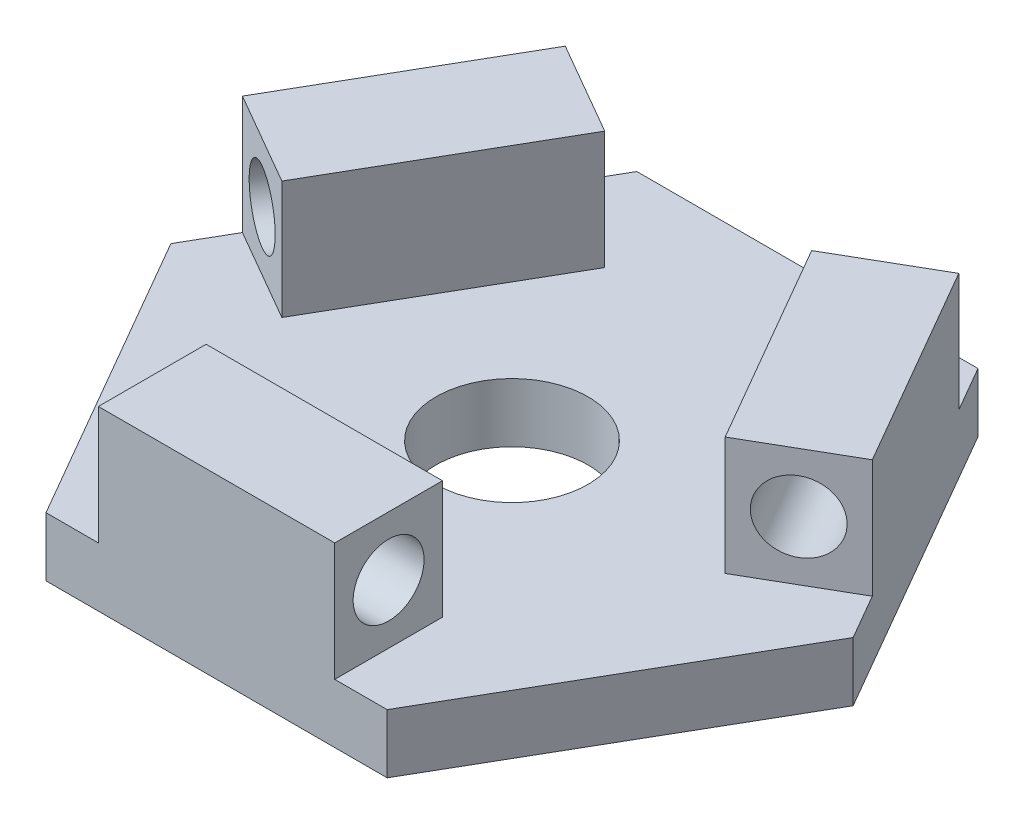
SolidWorks part; units mm, degrees
ref_plane "Front Plane" through (0, 0, 0) normal (0, 0, 1) x (1, 0, 0)
ref_plane "Top Plane" through (0, 0, 0) normal (0, 1, 0) x (1, 0, 0)
ref_plane "Right Plane" through (0, 0, 0) normal (1, 0, 0) x (0, 0, -1)
sketch "Sketch1" plane through (0, 0, 0) normal (0, 1, 0) x (1, 0, 0)
  line L1 (14.4338, 25) -> (-14.4338, 25)
  line L2 (-14.4338, 25) -> (-28.8675, 0)
  line L3 (-28.8675, 0) -> (-14.4338, -25)
  line L4 (-14.4338, -25) -> (14.4338, -25)
  line L5 (14.4338, -25) -> (28.8675, 0)
  line L6 (28.8675, 0) -> (14.4338, 25)
  circle A0 centre (0, 0) radius 25 construction
  dimension "D1" = 50
extrude "Boss-Extrude1" add sketch "Sketch1" along normal blind 5
sketch "Sketch4" plane through (0, 5, 0) normal (0, 1, 0) x (1, 0, 0)
  circle A0 centre (0, 0) radius 6.4308
extrude "Cut-Extrude2" cut sketch "Sketch4" against normal blind 10
sketch "Sketch2" plane through (0, 5, 0) normal (0, 1, 0) x (1, 0, 0)
  line L0 (0, -20.4418) -> (0, -25) construction
  line L1 (-10, -15.8837) -> (10, -15.8837)
  line L2 (-10, -15.8837) -> (-10, -25)
  line L3 (-10, -25) -> (10, -25)
  line L4 (10, -15.8837) -> (10, -25)
  line L5 (-10, -15.8837) -> (10, -25) construction
  line L6 (-10, -25) -> (10, -15.8837) construction
  line L7 (-14.4338, -25) -> (14.4338, -25) construction
  point P0 (0, -20.4418)
  dimension "D1" = 20
extrude "Boss-Extrude2" add sketch "Sketch2" along normal blind 10
sketch "Sketch3" plane through (10, 0, 0) normal (1, 0, 0) x (0, 0, -1)
  line L0 (-20.4418, 15) -> (-20.4418, 5) construction
  line L1 (-25, 15) -> (-15.8837, 15) construction
  line L2 (-25, 5) -> (-15.8837, 5) construction
  line L3 (-25, 10) -> (-15.8837, 10) construction
  line L4 (-25, 15) -> (-25, 5) construction
  line L5 (-15.8837, 15) -> (-15.8837, 5) construction
  circle A0 centre (-20.4418, 10) radius 3
  dimension "D1" = 6
extrude "Cut-Extrude1" cut sketch "Sketch3" against normal through all
pattern_circular "CirPattern1" count 3 over 360 about axis through (0, 0, 0) along (0, 1, 0) of "Cut-Extrude1", "Boss-Extrude2"
